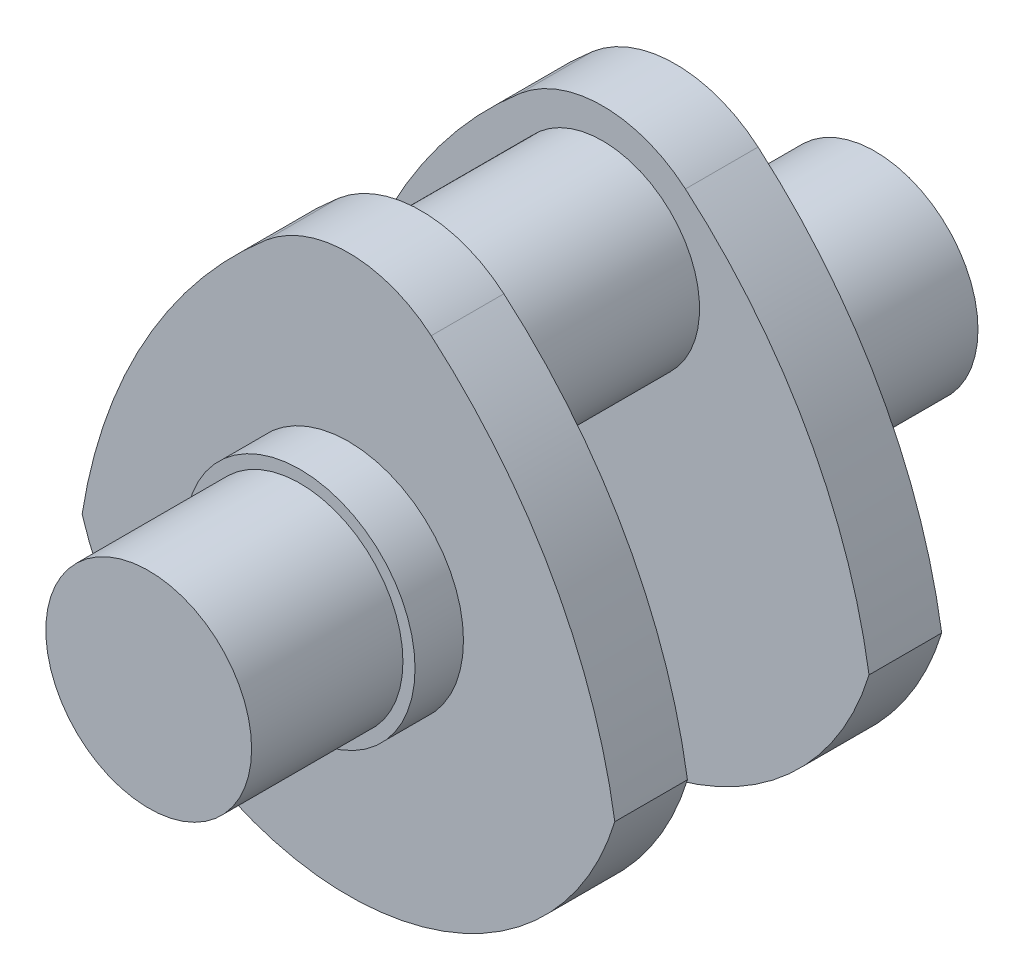
SolidWorks part; units mm, degrees
ref_plane "Front Plane" through (0, 0, 0) normal (0, 0, 1) x (1, 0, 0)
ref_plane "Top Plane" through (0, 0, 0) normal (0, 1, 0) x (1, 0, 0)
ref_plane "Right Plane" through (0, 0, 0) normal (1, 0, 0) x (0, 0, -1)
sketch "Sketch2" plane through (0, 0, 0) normal (0, 0, 1) x (1, 0, 0)
  circle A0 centre (0, 0) radius 17
  dimension "D1" = 34
extrude "Boss-Extrude1" add sketch "Sketch2" along normal blind 25
sketch "Sketch3" plane through (0, 0, 0) normal (0, 0, 1) x (1, 0, 0)
  circle A0 centre (0, 0) radius 19
  dimension "D1" = 38
extrude "Boss-Extrude2" add sketch "Sketch3" against normal blind 8
sketch "Sketch4" plane through (0, 0, -8) normal (0, 0, -1) x (-1, 0, 0)
  arc A0 (-44, -13.4164) -> (44, -13.4164) centre (0, 0) ccw
  arc A1 (13.6681, 40.9431) -> (-13.6681, 40.9431) centre (0, 25) ccw
  arc A2 (-13.6681, 40.9431) -> (-44, -13.4164) centre (44.9095, -27.3845) ccw
  arc A3 (13.6681, 40.9431) -> (44, -13.4164) centre (-44.9095, -27.3845) cw
  point P10 (0, 0)
  dimension "D2" = 46
  dimension "D4" = 42
  dimension "D5" = 90
  dimension "D6" = 90
  dimension "D1" = 88
  dimension "D3" = 25
extrude "Boss-Extrude3" add sketch "Sketch4" along normal blind 12
sketch "Sketch5" plane through (0, 0, -20) normal (0, 0, -1) x (-1, 0, 0)
  circle A0 centre (0, 25) radius 16
  point P2 (0, 0)
  dimension "D1" = 32
  dimension "D2" = 25
extrude "Boss-Extrude4" add sketch "Sketch5" along normal blind 15
mirror "Mirror1" about plane through (0, 25, -35) normal (0, 0, -1) of bodies 104
